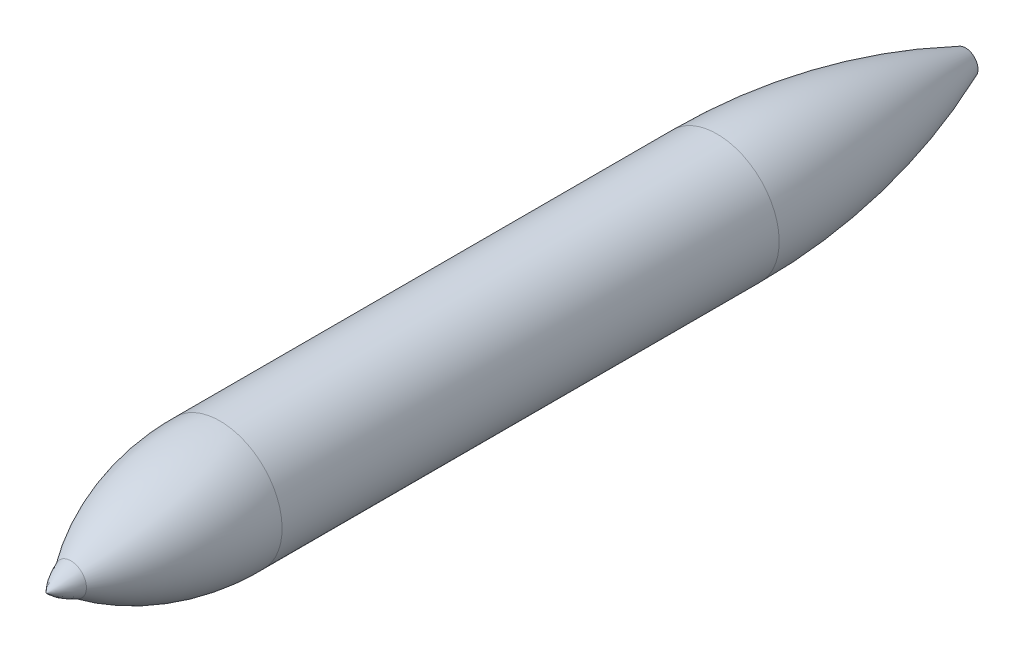
SolidWorks part; units mm, degrees
ref_plane "Front Plane" through (0, 0, 0) normal (0, 0, 1) x (1, 0, 0)
ref_plane "Top Plane" through (0, 0, 0) normal (0, 1, 0) x (1, 0, 0)
ref_plane "Right Plane" through (0, 0, 0) normal (1, 0, 0) x (0, 0, -1)
sketch "Sketch2" plane through (0, 0, 0) normal (1, 0, 0) x (0, 0, -1)
  line L0 (-700, 0) -> (2000, 0) construction
  line L1 (-600, 62.7008) -> (-600, 0) construction
  line L2 (0, 250) -> (0, 0) construction
  line L3 (2000, 250) -> (2000, 0) construction
  line L4 (0, 250) -> (2000, 250)
  line L5 (2000, 0) -> (3138.4814, 0) construction
  line L6 (3000, 50) -> (3000, 0)
  line L7 (-0.2587, 220) -> (2000, 220)
  line L8 (2970, 29.916) -> (2970, 0)
  line L9 (-700, 0) -> (-654.9615, 0)
  line L10 (2970, 0) -> (3000, 0)
  arc A1 (-600, 62.7008) -> (0, 250) centre (-17.1145, -749.8535) cw
  arc A2 (2000, 250) -> (3000, 50) centre (2000, -2350) cw
  arc A4 (-586.2913, 35.6003) -> (-0.2587, 220) centre (-17.1145, -749.8535) cw
  arc A5 (2000, 220) -> (2970, 29.916) centre (2000, -2350) cw
  arc A6 (-700, 0) -> (-600, 62.7008) centre (-515.4874, -183.1805) cw
  arc A7 (-654.9615, 0) -> (-586.2913, 35.6003) centre (-520.9479, -174.4716) cw
  arc A8 (-678.5138, -20.9366) -> (-586.2913, 35.6003) centre (-520.9479, -174.4716) cw construction
  arc A9 (-700, 0) -> (-600, 62.7008) centre (-520.9479, -174.4716) cw construction
  point P12 (3000, 25)
  dimension "D6" = 50
  dimension "D8" = 260
  dimension "D9" = 1000
  dimension "D10" = 2600
  dimension "D1" = 100
  dimension "D2" = 600
  dimension "D3" = 2000
  dimension "D4" = 250
  dimension "D5" = 250
  dimension "D7" = 1000
  dimension "D11" = 30
revolve "Revolve1" add sketch "Sketch2" angle 360 about L10
